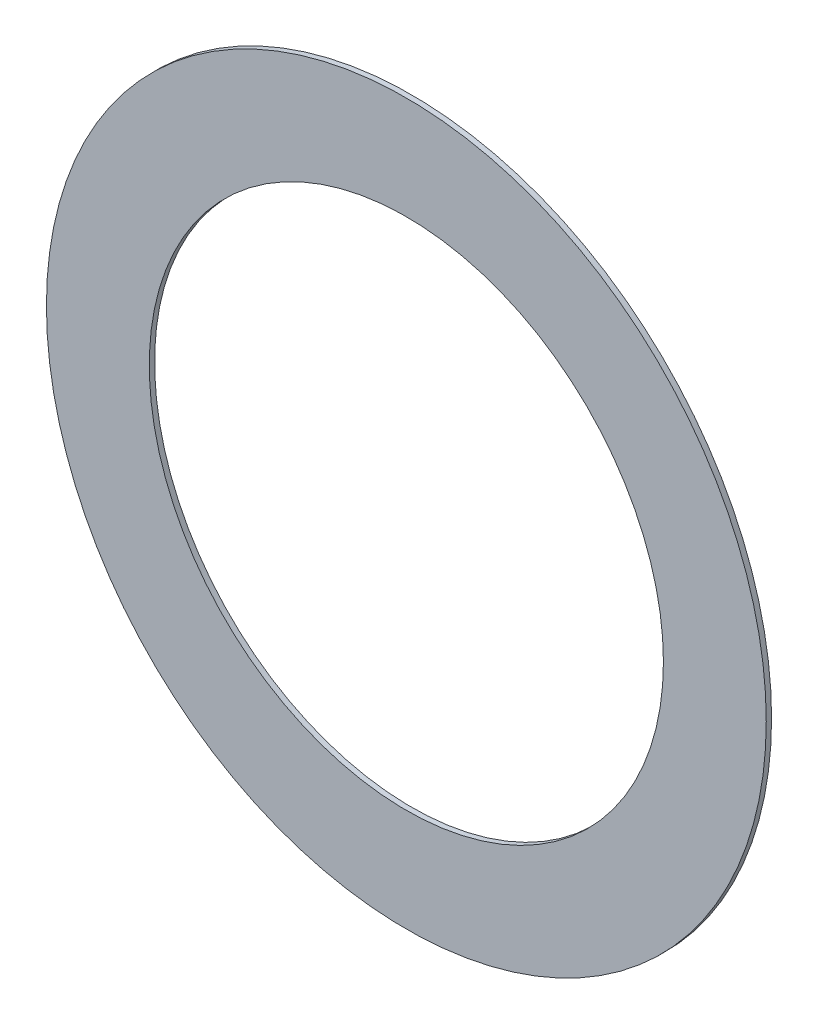
SolidWorks part; units mm, degrees
ref_plane "Front Plane" through (0, 0, 0) normal (0, 0, 1) x (1, 0, 0)
ref_plane "Top Plane" through (0, 0, 0) normal (0, 1, 0) x (1, 0, 0)
ref_plane "Right Plane" through (0, 0, 0) normal (1, 0, 0) x (0, 0, -1)
sketch "Sketch1" plane through (0, 0, 0) normal (0, 0, 1) x (1, 0, 0)
  circle A0 centre (0, 0) radius 203
  circle A1 centre (0, 0) radius 145
extrude "Gasket" add sketch "Sketch1" along normal blind 3
